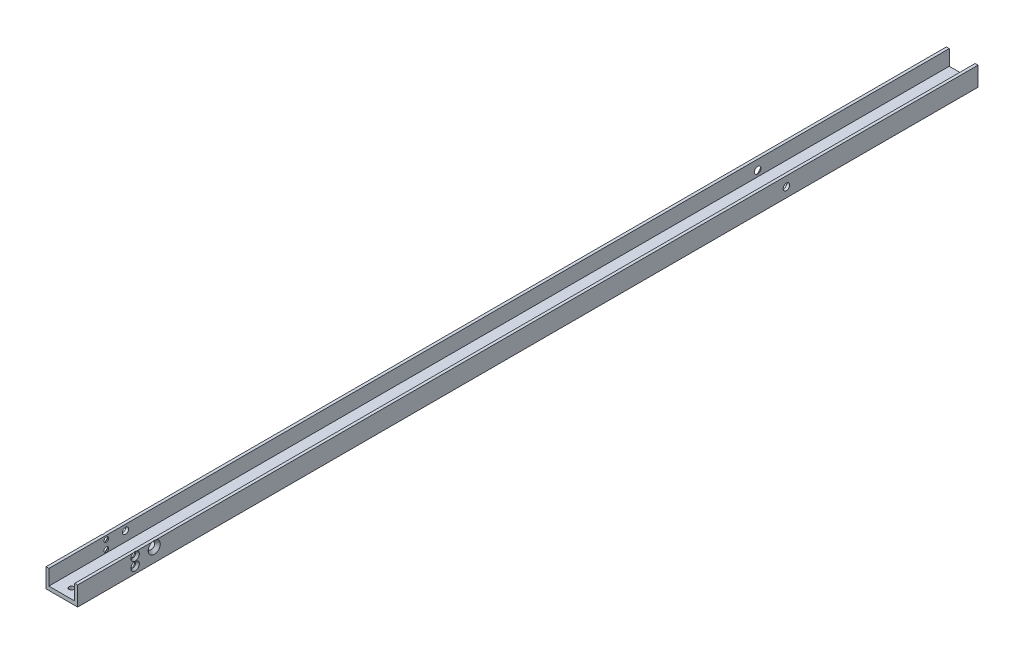
SolidWorks part; units mm, degrees
material "Alliage 1060"
ref_plane "Plan de face" through (0, 0, 0) normal (0, 0, 1) x (1, 0, 0)
ref_plane "Plan de dessus" through (0, 0, 0) normal (0, 1, 0) x (1, 0, 0)
ref_plane "Plan de droite" through (0, 0, 0) normal (1, 0, 0) x (0, 0, -1)
sketch "Esquisse1" plane through (0, 0, 0) normal (0, 0, 1) x (1, 0, 0)
  line L0 (-8.25, 0) -> (8.25, 0)
  line L1 (8.25, 0) -> (8.25, 10)
  line L2 (8.25, 10) -> (6.75, 10)
  line L3 (6.75, 10) -> (6.75, 2)
  line L4 (6.75, 2) -> (-6.75, 2)
  line L5 (0, 6.472) -> (0, -3.1073) construction
  line L6 (-6.75, 10) -> (-6.75, 2)
  line L7 (-8.25, 10) -> (-6.75, 10)
  line L8 (-8.25, 0) -> (-8.25, 10)
  point P10 (0, 2)
  point P13 (0, 0)
  dimension "D1" = 16.5
  dimension "D2" = 10
  dimension "D3" = 1.5
  dimension "D4" = 2
extrude "Boss.-Extru.1" add sketch "Esquisse1" along normal blind 470
sketch "Esquisse2" plane through (8.25, 0, 0) normal (1, 0, 0) x (0, 0, -1)
  line L0 (-440, 3.5) -> (-440, 13.011) construction
  line L1 (-470, 0) -> (-470, 10) construction
  line L2 (-470, 10) -> (0, 10) construction
  line L3 (-470, 2) -> (0, 2) construction
  line L5 (-470, 0) -> (0, 0) construction
  circle A0 centre (-440, 8) radius 1.15
  circle A1 centre (-440, 3.5) radius 1.15
  circle A2 centre (-430, 7) radius 1.6
  circle A3 centre (-441.25, 3.5) radius 1.15 construction
  circle A4 centre (-438.75, 5) radius 1.15 construction
  dimension "D1" = 2.3
  dimension "D2" = 2.3
  dimension "D3" = 30
  dimension "D6" = 3.2
  dimension "D9" = 2.3
  dimension "D10" = 2.3
  dimension "D4" = 2
  dimension "D5" = 4.5
  dimension "D7" = 40
  dimension "D8" = 5
  dimension "D11" = 1.25
  dimension "D12" = 1.25
  dimension "D13" = 3.5
  dimension "D14" = 1.5
extrude "Enlèv. mat.-Extru.1" cut sketch "Esquisse2" against normal through all
hole_wizard "Trou pour taraudage pour trou taraudé M31" positions "Esquisse3" profile "Esquisse4" hole size "M3" standard "ISO" end condition through all
sketch "Esquisse3" plane through (0, 2, 0) normal (0, 1, 0) x (1, 0, 0)
  line L0 (6.75, -470) -> (-6.75, -470) construction
  line L2 (0, -545.3962) -> (0, -539.2293) construction
  point P2 (0, -465)
  dimension "D2" = 5
sketch "Esquisse4" plane through (0, 2, 465) normal (1, 0, 0) x (0, 0, 1)
  line L0 (0, 0) -> (0, 2)
  line L1 (0, 2) -> (1.25, 2)
  line L2 (1.25, 2) -> (1.25, 0)
  line L5 (1.25, 0) -> (0, 0)
  line L11 (0, -6.35) -> (0, 107.95) construction
  dimension "Diamètre du perçage jusqu'au prochain" = 2.5
  dimension "Profondeur du perçage jusqu'au prochain" = 2
sketch "Esquisse5" plane through (0, 2, 0) normal (0, 1, 0) x (1, 0, 0)
  line L0 (0, -467.2445) -> (0, -475.452) construction
  line L1 (6.75, -470) -> (6.75, 0) construction
  line L2 (-6.75, -470) -> (-6.75, 0) construction
  circle A0 centre (0, -467.2445) radius 1.25
  dimension "D1" = 2.5
extrude "Enlèv. mat.-Extru.2" [suppressed] cut sketch "Esquisse5" against normal through all
hole_wizard "Formsenkung für M2 Senkschraube mit Schlitz/Kreuzschlitz3" positions "Skizze9" profile "Skizze8" countersink size "M2" standard "ANSI Metrisch"
sketch "Skizze9" plane through (8.25, 0, 0) normal (1, 0, 0) x (0, 0, -1)
  point P0 (-440, 3.5)
  point P3 (-440, 8)
sketch "Skizze8" plane through (8.25, 3.5, 440) normal (0, 1, 0) x (0, 0, -1)
  line L0 (0, 0) -> (0, 5.721)
  line L1 (0, 5.721) -> (1.2, 5)
  line L2 (1.2, 5) -> (1.2, 1)
  line L3 (1.2, 1) -> (2.2, 0)
  line L5 (2.2, 0) -> (0, 0)
  line L6 (-1.2, 1) -> (-2.2, 0) construction
  line L10 (0, 5.721) -> (-1.2, 5) construction
  line L11 (0, -6.35) -> (0, 107.95) construction
  dimension "Bohrerdurchmesser" = 2.4
  dimension "Bohrungstiefe" = 5
  dimension "Senkdurchmesser (Oben)" = 4.4
  dimension "Senkwinkel (Oben)" = 90
  dimension "Spitzenwinkel" = 118
hole_wizard "Formsenkung für M2 Senkschraube mit Schlitz/Kreuzschlitz4" positions "Skizze10" profile "Skizze11" countersink size "M2" standard "ANSI Metrisch"
sketch "Skizze10" plane through (-8.25, 0, 0) normal (-1, 0, 0) x (0, 0, 1)
  point P0 (440, 8)
  point P3 (440, 3.5)
sketch "Skizze11" plane through (-8.25, 8, 440) normal (0, 1, 0) x (0, 0, 1)
  line L0 (0, 0) -> (0, 5.721)
  line L1 (0, 5.721) -> (1.2, 5)
  line L2 (1.2, 5) -> (1.2, 1)
  line L3 (1.2, 1) -> (2.2, 0)
  line L5 (2.2, 0) -> (0, 0)
  line L6 (-1.2, 1) -> (-2.2, 0) construction
  line L10 (0, 5.721) -> (-1.2, 5) construction
  line L11 (0, -6.35) -> (0, 107.95) construction
  dimension "Bohrerdurchmesser" = 2.4
  dimension "Bohrungstiefe" = 5
  dimension "Senkdurchmesser (Oben)" = 4.4
  dimension "Senkwinkel (Oben)" = 90
  dimension "Spitzenwinkel" = 118
hole_wizard "Formsenkung für M3 Senkschraube mit Schlitz/Kreuzschlitz1" positions "Skizze12" profile "Skizze13" countersink size "M3" standard "ANSI Metrisch"
sketch "Skizze12" plane through (8.25, 0, 0) normal (1, 0, 0) x (0, 0, -1)
  point P0 (-430, 7)
sketch "Skizze13" plane through (8.25, 7, 430) normal (0, 1, 0) x (0, 0, -1)
  line L0 (0, 0) -> (0, 6.0215)
  line L1 (0, 6.0215) -> (1.7, 5)
  line L2 (1.7, 5) -> (1.7, 1.45)
  line L3 (1.7, 1.45) -> (3.15, 0)
  line L5 (3.15, 0) -> (0, 0)
  line L6 (-1.7, 1.45) -> (-3.15, 0) construction
  line L10 (0, 6.0215) -> (-1.7, 5) construction
  line L11 (0, -6.35) -> (0, 107.95) construction
  dimension "Bohrerdurchmesser" = 3.4
  dimension "Bohrungstiefe" = 5
  dimension "Senkdurchmesser (Oben)" = 6.3
  dimension "Senkwinkel (Oben)" = 90
  dimension "Spitzenwinkel" = 118
hole_wizard "Formsenkung für M3 Senkschraube mit Schlitz/Kreuzschlitz2" positions "Skizze4" profile "Skizze2" countersink size "M3" standard "ANSI Metrisch" end condition through all
sketch "Skizze4" plane through (-8.25, -1.5, 0) normal (1, 0, 0) x (0, 0, -1)
  line L6 (0, 11.5) -> (0, 1.5) construction
  line L7 (-470, 1.5) -> (0, 1.5) construction
  point P0 (-100, 6.5)
  point P15 (-99.0843, 6.5699)
  dimension "D1" = 100
  dimension "D2" = 5
sketch "Skizze2" plane through (-8.25, 5, 100) normal (0, 1, 0) x (0, 0, 1)
  line L0 (0, 0) -> (0, 16.6508)
  line L1 (0, 16.6508) -> (1.7, 16.6508)
  line L2 (1.7, 16.6508) -> (1.7, 1.45)
  line L3 (1.7, 1.45) -> (3.15, 0)
  line L5 (3.15, 0) -> (0, 0)
  line L6 (-1.7, 1.45) -> (-3.15, 0) construction
  line L11 (0, -6.35) -> (0, 107.95) construction
  dimension "Bohrerdurchmesser" = 3.4
  dimension "Bohrungstiefe" = 16.6508
  dimension "Senkdurchmesser (Oben)" = 6.3
  dimension "Senkwinkel (Oben)" = 90
